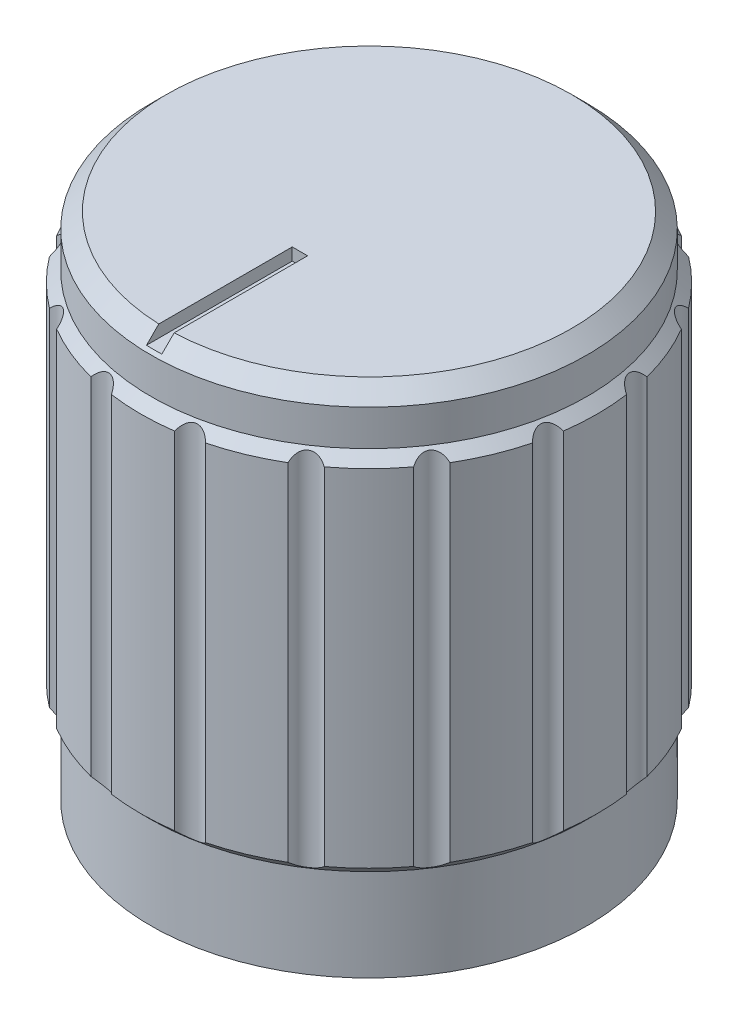
SolidWorks part; units mm, degrees
material "6061-T6 (SS)"
ref_plane "Front Plane" through (0, 0, 0) normal (0, 0, 1) x (1, 0, 0)
ref_plane "Top Plane" through (0, 0, 0) normal (0, 1, 0) x (1, 0, 0)
ref_plane "Right Plane" through (0, 0, 0) normal (1, 0, 0) x (0, 0, -1)
ref_plane "Plane1" through (0, 17, 0) normal (0, 1, 0) x (1, 0, 0)
sketch "Sketch50" plane through (0, 17, 0) normal (0, 1, 0) x (1, 0, 0)
  line L1 (-2.5981, 1.5) -> (2.5981, 1.5)
  line L2 (0, 0) -> (0, 1.5) construction
  line L3 (0, 0) -> (0, -2.25) construction
  line L4 (0.25, -2.25) -> (-0.25, -2.25) construction
  line L5 (0, -2.25) -> (0, -7.25) construction
  line L6 (0.25, -7.25) -> (-0.25, -7.25) construction
  line L7 (0.25, -7.25) -> (0.25, -2.25) construction
  line L8 (-0.25, -7.25) -> (-0.25, -2.25) construction
  arc A1 (-2.5981, 1.5) -> (2.5981, 1.5) centre (0, 0) ccw
  circle A2 centre (0, 0) radius 6
  point P1 (-2.4709, 1.7014)
  dimension "D4" = 12
  dimension "D5" = 3
  dimension "D1" = 0.5
  dimension "D2" = 3.75
  dimension "D3" = 5
  dimension "D6" = 1.5
extrude "Boss-Extrude31" add sketch "Sketch50" along normal blind 12 separate body
sketch "Sketch51" plane through (0, 17, 0) normal (0, -1, 0) x (1, 0, 0)
  circle A0 centre (0, 0) radius 4
  circle A1 centre (0, 0) radius 5
  dimension "D1" = 8
  dimension "D2" = 10
extrude "Cut-Extrude11" cut sketch "Sketch51" against normal blind 10
sketch "Sketch52" plane through (0, 0, 0) normal (0, 0, 1) x (1, 0, 0)
  line L0 (0, 0) -> (0, 14.4) construction
  line L1 (0, 14.4) -> (0, 29) construction
  line L2 (6, 29) -> (-6, 29) construction
  line L3 (0, 29) -> (0, 31)
  line L4 (0, 31) -> (6.6, 31)
  line L5 (6.6, 31) -> (6.6, 30.5) construction
  line L6 (6.6, 30.5) -> (7.1, 30.5) construction
  line L7 (6.6, 31) -> (7.1, 30.5)
  line L8 (7.1, 30.5) -> (7.1, 29.33)
  line L9 (7.1, 29.33) -> (7.1, 29) construction
  line L10 (7.1, 29) -> (7.43, 29) construction
  line L11 (7.43, 29) -> (7.1, 29.33)
  line L12 (7.1, 29) -> (7.1, 17.73) construction
  line L13 (7.1, 17.73) -> (7.43, 17.73) construction
  line L14 (7.43, 17.73) -> (7.1, 17.4)
  line L15 (7.1, 17.4) -> (7.1, 17.73) construction
  line L16 (7.43, 29) -> (7.43, 17.73)
  line L17 (7.1, 17.4) -> (7.1, 14.4)
  line L18 (0, 14.4) -> (6, 14.4) construction
  line L19 (0, 29) -> (6, 29)
  line L20 (6, 29) -> (6, 14.4)
  line L21 (6, 14.4) -> (7.1, 14.4)
  line L23 (-6, 17) -> (6, 17) construction
  dimension "D1" = 2
  dimension "D2" = 0.5
  dimension "D3" = 7.1
  dimension "D4" = 3
  dimension "D5" = 7.43
  dimension "D6" = 2
  dimension "D7" = 16.6
  dimension "D8" = 2.6
revolve "Revolve2" add sketch "Sketch52" angle 360 about L3
sketch "Sketch53" plane through (0, 31, 0) normal (0, 1, 0) x (1, 0, 0)
  line L0 (0.25, -2.25) -> (-0.25, -2.25) construction
  line L1 (0.25, -7.25) -> (-0.25, -7.25) construction
  line L2 (0.25, -7.25) -> (0.25, -2.25) construction
  line L3 (-0.25, -7.25) -> (-0.25, -2.25) construction
  line L4 (0.25, -2.25) -> (-0.25, -2.25)
  line L5 (0.25, -7.25) -> (-0.25, -7.25)
  line L6 (0.25, -7.25) -> (0.25, -2.25)
  line L7 (-0.25, -7.25) -> (-0.25, -2.25)
extrude "Cut-Extrude12" cut sketch "Sketch53" against normal blind 0.4
sketch "Sketch54" plane through (0, 31, 0) normal (0, 1, 0) x (1, 0, 0)
  line L0 (0, 0) -> (0, 7) construction
  line L1 (0, 0) -> (1.4495, 7.2872) construction
  line L2 (1.4495, 7.2872) -> (1.4983, 7.5324) construction
  arc A0 (-0.25, -6.9955) -> (0.25, -6.9955) centre (0, 0) ccw construction
  circle A1 centre (0, 0) radius 7.43 construction
  circle A2 centre (1.4983, 7.5324) radius 0.5
  dimension "D1" = 0.25
  dimension "D2" = 1
  dimension "D3" = 11.25
extrude "Cut-Extrude13" cut sketch "Sketch54" against normal up to surface (16.6 mm away) up to face at (0, 14.4, -7.1)
pattern_circular "CirPattern1" count 16 over 360 about axis through (0, 0, 0) along (0, 1, 0) of "Cut-Extrude13"
